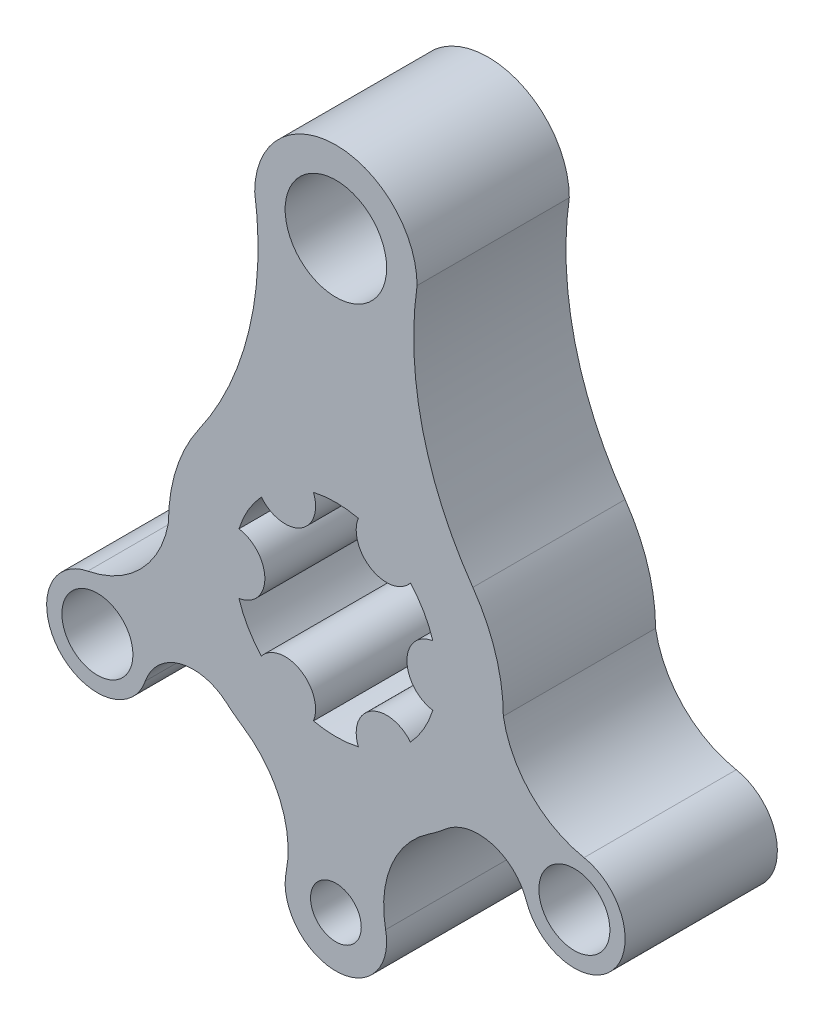
SolidWorks part; units mm, degrees
ref_plane "Front Plane" through (0, 0, 0) normal (0, 0, 1) x (1, 0, 0)
ref_plane "Top Plane" through (0, 0, 0) normal (0, 1, 0) x (1, 0, 0)
ref_plane "Right Plane" through (0, 0, 0) normal (1, 0, 0) x (0, 0, -1)
sketch "Sketch1" plane through (0, 0, 0) normal (0, 0, 1) x (1, 0, 0)
  line L0 (0, 0) -> (0, 23656.1094) construction
  line L1 (0, 0) -> (23656.1094, 0) construction
  line L2 (-44.1103, 65) -> (44.1103, 65) construction
  arc A0 (14.6874, -13.575) -> (19.1, -5.9321) centre (0, 0) ccw
  arc A1 (19.1, 5.9321) -> (19.1, -5.9321) centre (20, 0) ccw
  arc A2 (14.6874, -13.575) -> (4.4126, -19.5071) centre (10, -17.3205) ccw
  arc A3 (-4.4126, -19.5071) -> (-14.6874, -13.575) centre (-10, -17.3205) ccw
  arc A4 (-19.1, -5.9321) -> (-19.1, 5.9321) centre (-20, 0) ccw
  arc A5 (-14.6874, 13.575) -> (-4.4126, 19.5071) centre (-10, 17.3205) ccw
  arc A6 (4.4126, 19.5071) -> (14.6874, 13.575) centre (10, 17.3205) ccw
  circle A7 centre (0, 65) radius 10
  circle A8 centre (0, -50) radius 5
  circle A9 centre (47, -26) radius 7
  circle A10 centre (-47, -26) radius 7
  arc A11 (-9.804, -48.03) -> (9.804, -48.03) centre (0, -50) ccw
  arc A12 (-48.8999, -16.1821) -> (-37.5509, -29.2733) centre (-47, -26) ccw
  arc A13 (37.5509, -29.2733) -> (48.8999, -16.1821) centre (47, -26) ccw
  arc A14 (15.5763, 61.3421) -> (-15.5763, 61.3421) centre (0, 65) ccw
  arc A15 (-26.9908, 18.9867) -> (-33, 0) centre (0, 0) ccw
  arc A16 (-16, 65) -> (-26.9908, 18.9867) centre (-79.3367, 55.8094) cw
  arc A17 (-33, 0) -> (-48.8999, -16.1821) centre (-52.6996, 3.4536) cw
  arc A18 (-37.5509, -29.2733) -> (-21.5665, -24.9777) centre (-28.1018, -32.5467) cw
  arc A19 (-18.3132, -27.4523) -> (-9.804, -48.03) centre (-29.4121, -44.09) cw
  arc A20 (18.3132, -27.4523) -> (9.804, -48.03) centre (29.4121, -44.09) ccw
  arc A21 (37.5509, -29.2733) -> (21.5665, -24.9777) centre (28.1018, -32.5467) ccw
  arc A22 (33, 0) -> (48.8999, -16.1821) centre (52.6996, 3.4536) ccw
  arc A23 (16, 65) -> (26.9908, 18.9867) centre (79.3367, 55.8094) ccw
  arc A24 (-4.4126, -19.5071) -> (4.4126, -19.5071) centre (0, 0) ccw
  arc A25 (-19.1, -5.9321) -> (-14.6874, -13.575) centre (0, 0) ccw
  arc A26 (-14.6874, 13.575) -> (-19.1, 5.9321) centre (0, 0) ccw
  arc A27 (4.4126, 19.5071) -> (-4.4126, 19.5071) centre (0, 0) ccw
  arc A28 (19.1, 5.9321) -> (14.6874, 13.575) centre (0, 0) ccw
  arc A29 (-21.5665, -24.9777) -> (0, -33) centre (0, 0) ccw
  arc A30 (18.3132, -27.4523) -> (21.5665, -24.9777) centre (0, 0) ccw
  arc A31 (33, 0) -> (26.9908, 18.9867) centre (0, 0) ccw
  point P22 (0, 0)
  point P35 (0, 65)
  dimension "D1" = 40
  dimension "D2" = 12
  dimension "D3" = 20
  dimension "D5" = 10
  dimension "D6" = 26
  dimension "D9" = 14
  dimension "D10" = 20
  dimension "D11" = 32
  dimension "D12" = 20
  dimension "D13" = 66
  dimension "D14" = 64
  dimension "D15" = 20
  dimension "D16" = 10
  dimension "D17" = 20
  dimension "D4" = 65
  dimension "D7" = 24
  dimension "D8" = 47
extrude "Boss-Extrude1" add sketch "Sketch1" along normal mid plane 30
